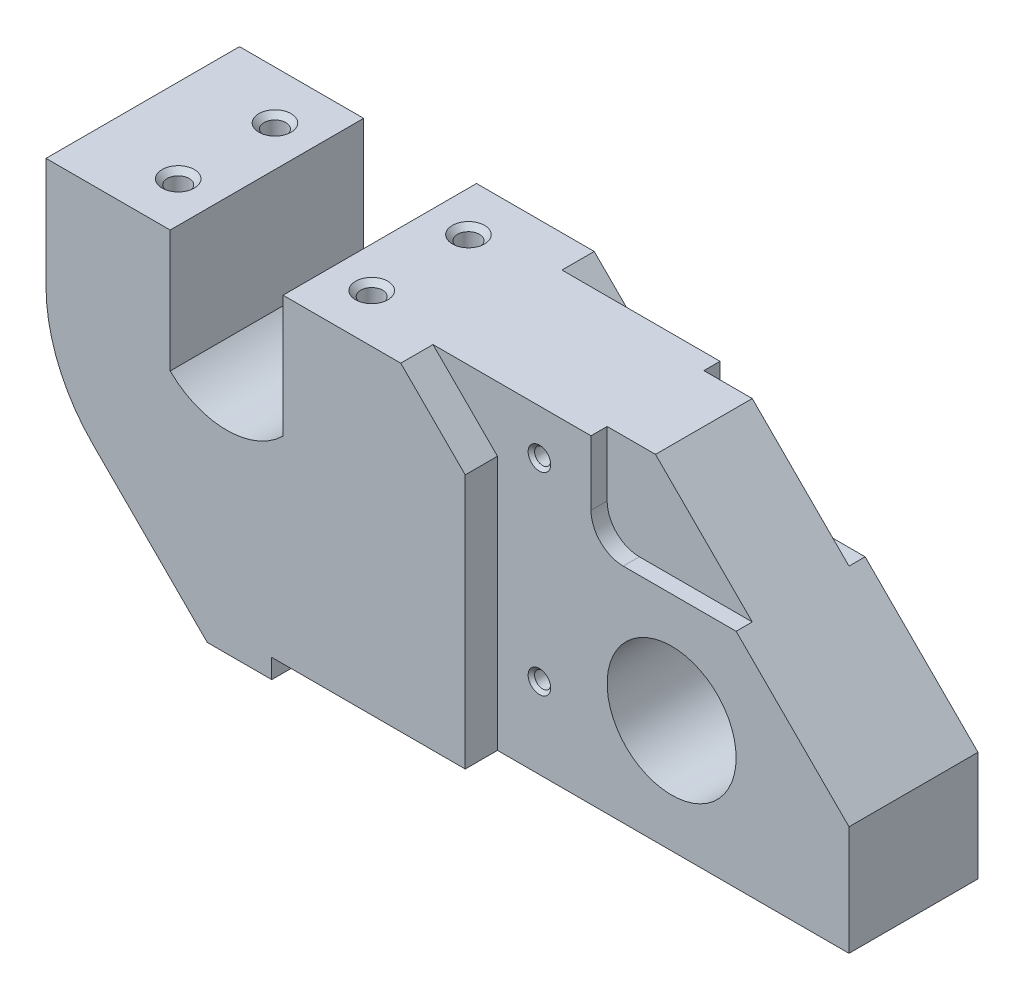
SolidWorks part; units mm, degrees
material "3.0205 (EN-AW 1200)"
ref_plane "Спереди" through (0, 0, 0) normal (0, 0, 1) x (1, 0, 0)
ref_plane "Сверху" through (0, 0, 0) normal (0, 1, 0) x (1, 0, 0)
ref_plane "Справа" through (0, 0, 0) normal (1, 0, 0) x (0, 0, -1)
sketch "Эскиз5" plane through (0, 0, 0) normal (0, 0, 1) x (1, 0, 0)
  line L2 (-56, 20) -> (-56, -85)
  line L4 (-56, -85) -> (183, -85)
  line L5 (55, 0) -> (-55, 0) construction
  line L6 (183, -85) -> (183, 20)
  line L11 (-56, 20) -> (183, 20)
  circle A0 centre (0, 0) radius 25 construction
  dimension "D6" = 50
  dimension "D4" = 85
  dimension "D7" = 105
  dimension "D10" = 239
  dimension "D11" = 56
extrude "Бобышка-Вытянуть1" add sketch "Эскиз5" along normal mid plane 40
sketch "Эскиз10" plane through (0, 0, 20) normal (0, 0, 1) x (1, 0, 0)
  line L0 (-56, 20) -> (74, 20)
  line L2 (74, 20) -> (74, -79)
  line L5 (-56, 20) -> (-56, -85)
  line L7 (-56, -85) -> (14, -85)
  line L8 (-56, -85) -> (183, -85) construction
  line L9 (14, -85) -> (14, -79)
  line L10 (14, -79) -> (74, -79)
  dimension "D1" = 60
  dimension "D2" = 6
  dimension "D3" = 130
extrude "Бобышка-Вытянуть2" add sketch "Эскиз10" along normal blind 10
sketch "Эскиз4" plane through (0, 0, 0) normal (0, 0, 1) x (1, 0, 0)
  line L2 (0, 0) -> (0, 50000) construction
  line L4 (-17.5, 20) -> (17.5, 20)
  line L5 (-17.5, 20) -> (-17.5, -17.8536)
  line L6 (183, 20) -> (74, 20) construction
  line L7 (17.5, 20) -> (17.5, -17.8536)
  arc A2 (-17.5, -17.8536) -> (17.5, -17.8536) centre (0, 0) ccw
  dimension "D1" = 35
  dimension "D2" = 25
mirror "Зеркальное отражение1" about plane through (0, 0, 0) normal (0, 0, 1) of "Бобышка-Вытянуть2"
sketch "Эскиз8" plane through (0, 0, 20) normal (0, 0, 1) x (1, 0, 0)
  line L0 (14, -85) -> (183, -85) construction
  line L1 (14, -85) -> (183, -85)
  line L2 (14, -85) -> (14, -79)
  line L3 (14, -79) -> (183, -79)
  line L4 (183, -85) -> (183, -79)
  line L6 (183, -85) -> (183, 20) construction
  line L7 (-56, 20) -> (-56, -85) construction
  dimension "D1" = 6
  dimension "D2" = 70
extrude "Вырез-Вытянуть6" cut sketch "Эскиз8" against normal through all
extrude "Вырез-Вытянуть7" cut sketch "Эскиз4" against normal through all both and the other way through all
sketch "Эскиз13" plane through (0, -79, 0) normal (0, -1, 0) x (-1, 0, 0)
  line L0 (0, 0) -> (50000, 0) construction
  line L1 (-14, -30) -> (-14, 30) construction
  point P0 (-29, 17.5)
  point P2 (-29, -17.5)
  point P4 (-79, 0)
  point P6 (-169, 0)
  dimension "D1" = 35
  dimension "D2" = 50
  dimension "D3" = 90
  dimension "D4" = 15
hole_wizard "Отверстие обработанное метчиком M82" positions "Эскиз13" profile "Эскиз12" tap size "M8" standard "IS"
sketch "Эскиз12" plane through (29, -79, -17.5) normal (1, 0, 0) x (0, 0, -1)
  line L0 (0, 0) -> (0, 27.0429)
  line L1 (0, 27.0429) -> (3.4, 25)
  line L2 (3.4, 25) -> (3.4, 1.6)
  line L3 (3.4, 1.6) -> (5, 0)
  line L5 (5, 0) -> (0, 0)
  line L6 (-3.4, 1.6) -> (-5, 0) construction
  line L10 (0, 27.0429) -> (-3.4, 25) construction
  line L11 (0, -6.35) -> (0, 107.95) construction
  dimension "Диаметр сверла" = 6.8
  dimension "Глубина сверла" = 25
  dimension "Диаметр передней зенковки" = 10
  dimension "Угол передней зенковки" = 90
  dimension "Угол заточки сверла" = 118
cosmetic thread "Отверстие резьбы5" parameters "D1"=20, "D2"=8
cosmetic thread "Отверстие резьбы6" parameters "D1"=20, "D2"=8
cosmetic thread "Отверстие резьбы7" parameters "D1"=20, "D2"=8
cosmetic thread "Отверстие резьбы8" parameters "D1"=20, "D2"=8
chamfer "Фаска1" distance 65 angle 45 1 edges at (183, 20, 0)
chamfer "Фаска2" distance 20 angle 45 2 edges at (74, 20, 25) (74, 20, -25)
sketch "Эскиз14" plane through (0, 0, 20) normal (0, 0, 1) x (1, 0, 0)
  line L0 (118, 20) -> (103, 20)
  line L2 (103, -10) -> (148, -10)
  line L3 (183, -45) -> (118, 20) construction
  line L4 (148, -10) -> (118, 20)
  line L5 (103, -10) -> (103, 20)
  dimension "D1" = 45
  dimension "D2" = 30
extrude "Вырез-Вытянуть8" cut sketch "Эскиз14" against normal blind 5
sketch "Эскиз17" plane through (0, 20, 0) normal (0, 1, 0) x (1, 0, 0)
  line L0 (-17.5, -30) -> (-56, -30) construction
  line L1 (-56, -30) -> (-56, 30) construction
  line L3 (-30, -15) -> (-30, 15) construction
  line L5 (30, 15) -> (30, -15) construction
  line L6 (30, -15) -> (-30, -15) construction
  line L10 (-30, 15) -> (30, 15) construction
  point P0 (-30, -15)
  point P15 (30, -15)
  point P27 (-30, 15)
  point P51 (30, 15)
  dimension "D1" = 15
  dimension "D2" = 26
  dimension "D3" = 60
  dimension "D4" = 30
hole_wizard "Отверстие обработанное метчиком M81" positions "Эскиз17" profile "Эскиз16" tap size "M8" standard "ISO"
sketch "Эскиз16" plane through (-30, 20, 15) normal (1, 0, 0) x (0, 0, 1)
  line L0 (0, 0) -> (0, 26)
  line L1 (0, 26) -> (3.4, 23.9571)
  line L2 (3.4, 23.9571) -> (3.4, 1.6)
  line L3 (3.4, 1.6) -> (5, 0)
  line L5 (5, 0) -> (0, 0)
  line L6 (-3.4, 1.6) -> (-5, 0) construction
  line L10 (0, 26) -> (-3.4, 23.9571) construction
  line L11 (0, -6.35) -> (0, 107.95) construction
  dimension "Диаметр сверла" = 6.8
  dimension "Глубина сверла" = 26
  dimension "Диаметр передней зенковки" = 10
  dimension "Угол передней зенковки" = 90
  dimension "Угол заточки сверла" = 118
cosmetic thread "Отверстие резьбы9" parameters "D1"=22, "D2"=8
cosmetic thread "Отверстие резьбы10" parameters "D1"=22, "D2"=8
cosmetic thread "Отверстие резьбы11" parameters "D1"=22, "D2"=8
cosmetic thread "Отверстие резьбы12" parameters "D1"=22, "D2"=8
mirror "Зеркальное отражение2" about plane through (0, 0, 0) normal (0, 0, 1) of "Вырез-Вытянуть8"
sketch "Эскиз20" plane through (0, 0, 20) normal (0, 0, 1) x (1, 0, 0)
  line L0 (183, -79) -> (74, -79) construction
  line L1 (183, -79) -> (183, -45) construction
  point P0 (87, -54)
  point P2 (87, 6)
  dimension "D1" = 60
  dimension "D2" = 25
  dimension "D3" = 96
hole_wizard "Отверстие обработанное метчиком M61" positions "Эскиз20" profile "Эскиз19" tap size "M6" standard "ISO" end condition through all
cosmetic thread "Отверстие резьбы15" parameters "D2"=6
cosmetic thread "Отверстие резьбы16" parameters "D2"=6
sketch "Эскиз19" plane through (87, -54, 20) normal (1, 0, 0) x (0, -1, 0)
  line L0 (0, 0) -> (0, 50)
  line L1 (0, 50) -> (2.5, 50)
  line L2 (2.5, 50) -> (2.5, 1)
  line L3 (2.5, 1) -> (3.5, 0)
  line L5 (3.5, 0) -> (0, 0)
  line L6 (-2.5, 1) -> (-3.5, 0) construction
  line L11 (0, -6.35) -> (0, 107.95) construction
  dimension "Диаметр проходного сверла" = 5
  dimension "Глубина проходного сверла" = 50
  dimension "Диаметр передней зенковки" = 7
  dimension "Угол передней зенковки" = 90
mirror "Зеркальное отражение3" about plane through (0, 0, 0) normal (0, 0, 1) of "Отверстие обработанное метчиком M61"
cosmetic thread "Отверстие резьбы17" parameters "D2"=6
cosmetic thread "Отверстие резьбы18" parameters "D2"=6
sketch "Эскиз21" plane through (0, 0, 20) normal (0, 0, 1) x (1, 0, 0)
  line L0 (183, -79) -> (74, -79) construction
  line L1 (183, -79) -> (183, -45) construction
  circle A0 centre (128, -44) radius 20
  dimension "D2" = 40
  dimension "D1" = 35
  dimension "D3" = 55
extrude "Вырез-Вытянуть9" cut sketch "Эскиз21" against normal up to next
fillet "Скругление1" radius 10 2 edges at (103, -10, 17.5) (103, -10, -17.5)
chamfer "Фаска3" distance 50 angle 45 1 edges at (-56, -85, 0)
fillet "Скругление2" radius 50 1 edges at (-56, -35, 0)
